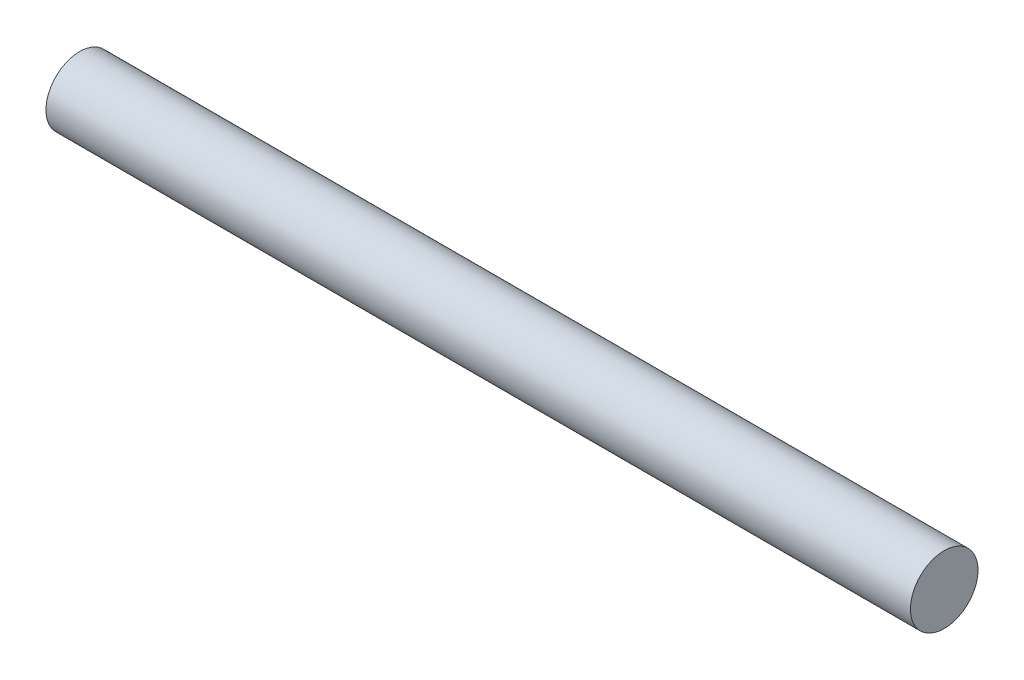
SolidWorks part; units mm, degrees
ref_plane "前视基准面" through (0, 0, 0) normal (0, 0, 1) x (1, 0, 0)
ref_plane "上视基准面" through (0, 0, 0) normal (0, 1, 0) x (1, 0, 0)
ref_plane "右视基准面" through (0, 0, 0) normal (1, 0, 0) x (0, 0, -1)
sketch "草图1" plane through (0, 0, 0) normal (1, 0, 0) x (0, 0, -1)
  circle A0 centre (0, 0) radius 12.5
  dimension "D1" = 25
extrude "凸台-拉伸1" add sketch "草图1" along normal blind 320
ref_plane "基准面1" through (160, 0, 0) normal (1, 0, 0) x (0, 0, -1)
